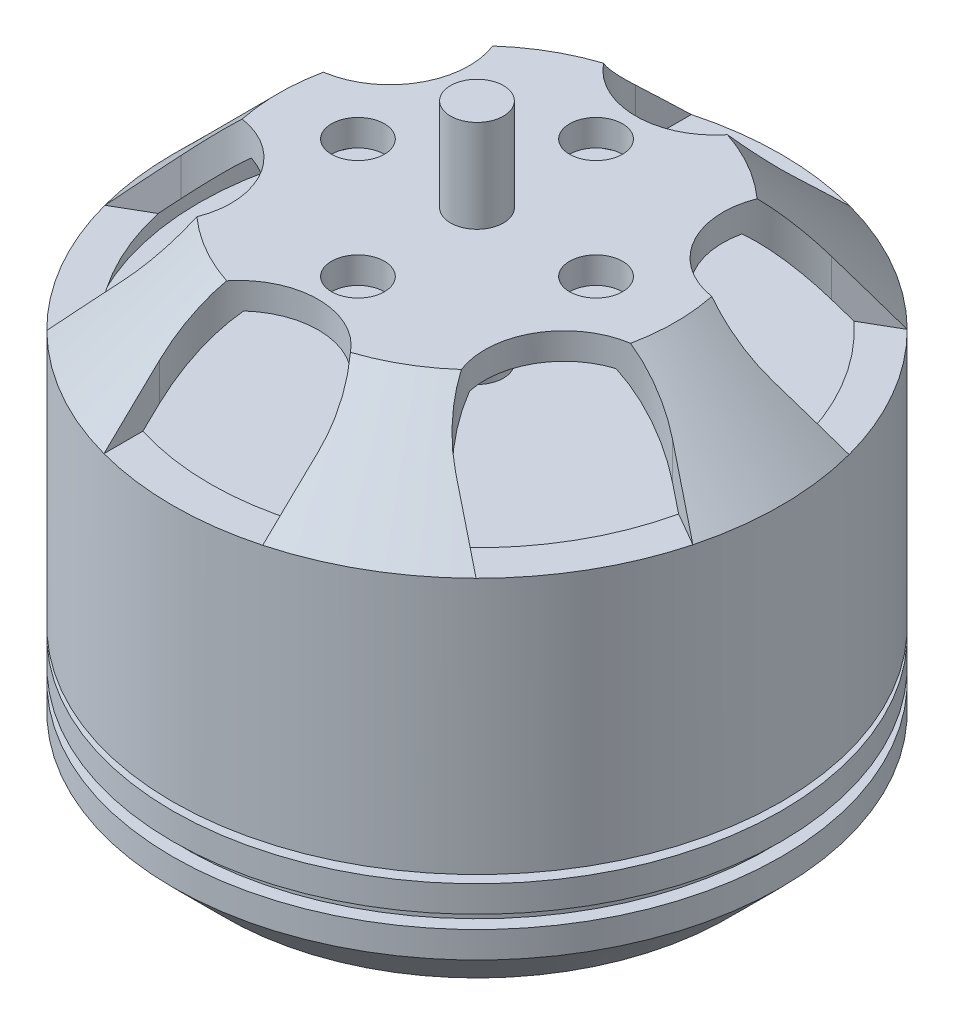
SolidWorks part; units mm, degrees
ref_plane "Front Plane" through (0, 0, 0) normal (0, 0, 1) x (1, 0, 0)
ref_plane "Top Plane" through (0, 0, 0) normal (0, 1, 0) x (1, 0, 0)
ref_plane "Right Plane" through (0, 0, 0) normal (1, 0, 0) x (0, 0, -1)
sketch "Sketch1" plane through (0, 0, 0) normal (0, 0, 1) x (1, 0, 0)
  line L0 (0, 22) -> (0, -1.8)
  line L1 (0, -1.8) -> (1, -1.8)
  line L2 (1, -1.8) -> (1, 0)
  line L3 (1, 0) -> (9.5, 0)
  line L4 (9.5, 0) -> (11.5, 2)
  line L5 (11.5, 2) -> (11.5, 3)
  line L6 (11.5, 14.5) -> (7.5, 18.5)
  line L7 (7.5, 18.5) -> (1, 18.5)
  line L8 (1, 18.5) -> (1, 22)
  line L9 (1, 22) -> (0, 22)
  line L11 (1, 16.5) -> (1, 13.4192)
  line L12 (1, 13.4192) -> (10.5, 13.4192)
  line L13 (10.5, 13.4192) -> (10.5, 14.0858)
  line L14 (10.5, 14.0858) -> (7.0858, 17.5)
  line L15 (7.0858, 17.5) -> (2, 17.5)
  line L16 (2, 17.5) -> (2, 16.5)
  line L17 (2, 16.5) -> (1, 16.5)
  line L18 (11.5, 4.8) -> (11.5, 14.5)
  line L19 (11.5, 3) -> (11, 3)
  line L21 (11.5, 3.5) -> (11, 3.5)
  line L22 (11, 3) -> (11, 3.5)
  line L23 (11.5, 4.5) -> (9.5, 4.5)
  line L25 (11.5, 4.8) -> (9.5, 4.8)
  line L26 (9.5, 4.5) -> (9.5, 4.8)
  line L27 (11.5, 3.5) -> (11.5, 4.5)
  point P13 (10.5, 13.7525)
  dimension "D1" = 23.8
  dimension "D2" = 1.8
  dimension "D3" = 45
  dimension "D4" = 2
  dimension "D5" = 1
  dimension "D6" = 1
  dimension "D7" = 3.5
  dimension "D8" = 45
  dimension "D9" = 11.5
  dimension "D10" = 4
  dimension "D11" = 1
  dimension "D12" = 1
  dimension "D13" = 1
  dimension "D14" = 1
  dimension "D15" = 1
  dimension "D16" = 1
  dimension "D17" = 1
  dimension "D18" = 0.5
  dimension "D19" = 0.5
  dimension "D20" = 2
  dimension "D21" = 0.3
revolve "Revolve1" add sketch "Sketch1" angle 360 about L0
sketch "Sketch2" plane through (0, 18.5, 0) normal (0, 1, 0) x (1, 0, 0)
  line L0 (-3, 9) -> (-3, 13.1523)
  line L1 (-3, 13.1523) -> (3, 13.1523)
  line L2 (3, 13.1523) -> (3, 9)
  line L3 (12.8902, 3.9781) -> (9.2942, 1.9019)
  line L4 (6.2942, 7.0981) -> (9.8902, 9.1742)
  line L5 (9.8902, 9.1742) -> (12.8902, 3.9781)
  line L6 (9.8902, -9.1742) -> (6.2942, -7.0981)
  line L7 (9.2942, -1.9019) -> (12.8902, -3.9781)
  line L8 (12.8902, -3.9781) -> (9.8902, -9.1742)
  line L9 (-3, -13.1523) -> (-3, -9)
  line L10 (3, -9) -> (3, -13.1523)
  line L11 (3, -13.1523) -> (-3, -13.1523)
  line L12 (-12.8902, -3.9781) -> (-9.2942, -1.9019)
  line L13 (-6.2942, -7.0981) -> (-9.8902, -9.1742)
  line L14 (-9.8902, -9.1742) -> (-12.8902, -3.9781)
  line L15 (-9.8902, 9.1742) -> (-6.2942, 7.0981)
  line L16 (-9.2942, 1.9019) -> (-12.8902, 3.9781)
  line L17 (-12.8902, 3.9781) -> (-9.8902, 9.1742)
  circle A0 centre (0, 0) radius 4.5 construction
  circle A1 centre (0, 0) radius 9 construction
  circle A2 centre (0, 4.5) radius 1
  arc A3 (-3, 9) -> (3, 9) centre (0, 9) ccw
  arc A4 (6.2942, 7.0981) -> (9.2942, 1.9019) centre (7.7942, 4.5) ccw
  arc A5 (9.2942, -1.9019) -> (6.2942, -7.0981) centre (7.7942, -4.5) ccw
  arc A6 (3, -9) -> (-3, -9) centre (0, -9) ccw
  arc A7 (-6.2942, -7.0981) -> (-9.2942, -1.9019) centre (-7.7942, -4.5) ccw
  arc A8 (-9.2942, 1.9019) -> (-6.2942, 7.0981) centre (-7.7942, 4.5) ccw
  circle A9 centre (4.5, 0) radius 1
  circle A10 centre (0, -4.5) radius 1
  circle A11 centre (-4.5, 0) radius 1
  dimension "D1" = 9
  dimension "D2" = 18
  dimension "D3" = 2
  dimension "D4" = 6
  dimension "D5" = 6
  dimension "D6" = 4
extrude "Cut-Extrude1" cut sketch "Sketch2" against normal blind 4
sketch "Sketch3" [suppressed] plane through (0, 0, 0) normal (0, -1, 0) x (1, 0, 0)
  circle A0 centre (0, 0) radius 6 construction
  circle A1 centre (0, 0) radius 8 construction
  circle A2 centre (0, 6) radius 1
  circle A3 centre (-6, 0) radius 1
  circle A4 centre (0, -6) radius 1
  circle A5 centre (6, 0) radius 1
  dimension "D1" = 12
  dimension "D2" = 16
  dimension "D3" = 2
extrude "Cut-Extrude2" [suppressed] cut sketch "Sketch3" against normal blind 3
sketch "Sketch4" plane through (0, 0, 0) normal (0, -1, 0) x (1, 0, 0)
  circle A0 centre (0, 0) radius 6 construction
  circle A1 centre (0, 0) radius 8 construction
  circle A2 centre (0, 6) radius 1
  circle A3 centre (0, -6) radius 1
  circle A4 centre (6, 0) radius 1
  circle A5 centre (-8, 0) radius 1
  dimension "D1" = 16
  dimension "D2" = 12
  dimension "D3" = 2
extrude "Cut-Extrude3" cut sketch "Sketch4" against normal blind 3
